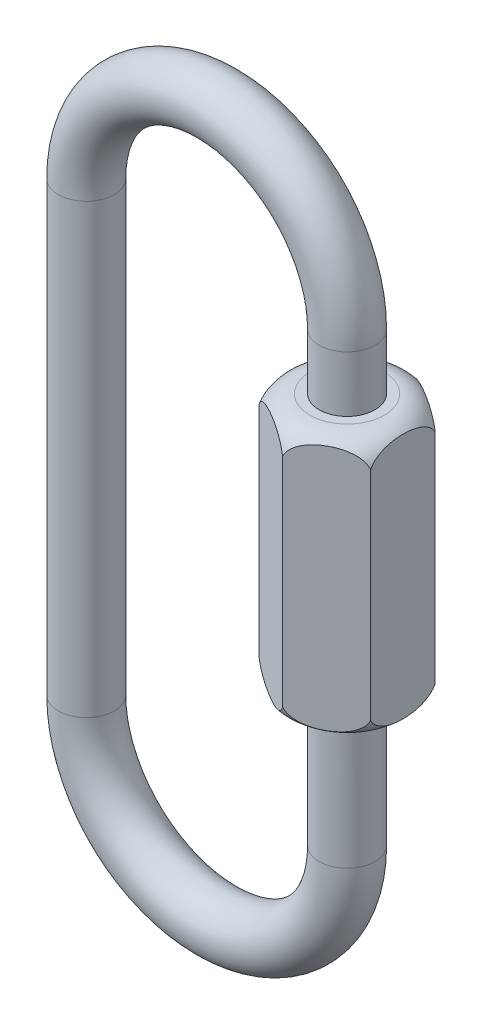
SolidWorks part; units mm, degrees
ref_plane "Front Plane" through (0, 0, 0) normal (0, 0, 1) x (1, 0, 0)
ref_plane "Top Plane" through (0, 0, 0) normal (0, 1, 0) x (1, 0, 0)
ref_plane "Right Plane" through (0, 0, 0) normal (1, 0, 0) x (0, 0, -1)
sketch "Sketch1" plane through (0, 0, 0) normal (1, 0, 0) x (0, 0, -1)
  circle A0 centre (0, 0) radius 1.5
  dimension "D1" = 3
sketch "Sketch2" plane through (0, 0, 0) normal (0, 0, 1) x (1, 0, 0)
  line L0 (0, -3.85) -> (0, 3.85) construction
  line L1 (55, 0) -> (-55, 0) construction
  line L3 (-7, 7) -> (-7, 31)
  line L4 (7, 7) -> (7, 31)
  arc A0 (7, 31) -> (-7, 31) centre (0, 31) ccw
  arc A1 (0, 0) -> (-7, 7) centre (0, 7) cw
  arc A2 (0, 0) -> (7, 7) centre (0, 7) ccw
  dimension "D4" = 14
  dimension "D5" = 7
  dimension "D6" = 7
  dimension "D1" = 38
sweep "Sweep1" add profiles "Sketch1" path "Sketch2"
ref_plane "Plane1" through (7, 31, 0) normal (0, 1, 0) x (-1, 0, 0)
sketch "Sketch3" plane through (7, 31, 0) normal (0, 1, 0) x (-1, 0, 0)
  line L0 (62, 0) -> (-48, 0) construction
  line L1 (-3, 1.7321) -> (-3, -1.7321)
  line L2 (-3, -1.7321) -> (0, -3.4641)
  line L3 (0, -3.4641) -> (3, -1.7321)
  line L4 (3, -1.7321) -> (3, 1.7321)
  line L5 (3, 1.7321) -> (0, 3.4641)
  line L6 (0, 3.4641) -> (-3, 1.7321)
  circle A0 centre (0, 0) radius 3 construction
  dimension "D1" = 6
extrude "Boss-Extrude1" add sketch "Sketch3" along direction (0, 1, 0) on the side against the normal blind 14 from offset 3 offset against normal yes
sketch "Sketch4" plane through (0, 0, 0) normal (0, 0, 1) x (1, 0, 0)
  line L0 (9, 14) -> (9, 12)
  line L1 (10.5, 26.5) -> (10.5, 15.5)
  line L2 (7, 28) -> (10, 28) construction
  line L3 (7, 7) -> (7, 31) construction
  line L5 (7, 14) -> (10, 14) construction
  line L9 (9, 30.0093) -> (12.5, 30.0093)
  line L10 (9, 30.0093) -> (9, 28)
  line L11 (9, 12) -> (12.5, 12)
  line L12 (12.5, 30.0093) -> (12.5, 12)
  arc A0 (10.5, 15.5) -> (9, 14) centre (9, 15.5) cw
  arc A1 (10.5, 26.5) -> (9, 28) centre (9, 26.5) ccw
  dimension "D1" = 1.5
  dimension "D2" = 3.5
  dimension "D3" = 2.0093
  dimension "D4" = 2
  dimension "D5" = 2
revolve "Cut-Revolve1" cut sketch "Sketch4" angle 360 about L4
sketch "Sketch5" plane through (0, 0, 0) normal (0, 0, 1) x (1, 0, 0)
  line L0 (0, 36.5) -> (9.9087, 36.5)
  line L1 (0, 1.5) -> (14.3357, 1.5)
  arc A0 (5.5, 31) -> (-5.5, 31) centre (0, 31) ccw construction
  arc A1 (-5.5, 7) -> (5.5, 7) centre (0, 7) ccw construction
  dimension "D1" = 35
